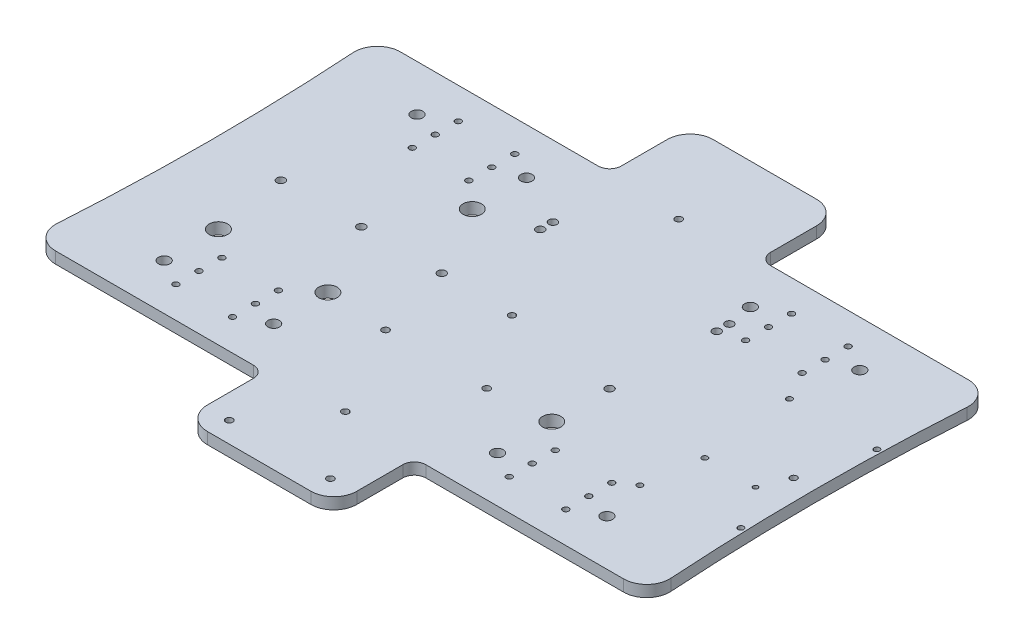
SolidWorks part; units mm, degrees
material "Acrylic (Medium-high impact)"
ref_plane "Front Plane" through (0, 0, 0) normal (0, 0, 1) x (1, 0, 0)
ref_plane "Top Plane" through (0, 0, 0) normal (0, 1, 0) x (1, 0, 0)
ref_plane "Right Plane" through (0, 0, 0) normal (1, 0, 0) x (0, 0, -1)
sketch "Sketch1" plane through (0, 0, 0) normal (0, 1, 0) x (1, 0, 0)
  line L0 (-142.875, -95.25) -> (-41.275, -95.25) construction
  line L2 (-174.625, -152.4) -> (-174.625, -139.7) construction
  line L3 (-174.625, 152.4) -> (-161.925, 152.4) construction
  line L4 (174.625, -152.4) -> (174.625, -139.7) construction
  line L5 (-174.625, -152.4) -> (174.625, 152.4) construction
  line L6 (-174.625, 152.4) -> (174.625, -152.4) construction
  line L7 (-92.075, -92.075) -> (92.075, -92.075) construction
  line L8 (-92.075, -92.075) -> (-92.075, 92.075) construction
  line L9 (-92.075, 92.075) -> (92.075, 92.075) construction
  line L10 (92.075, -92.075) -> (92.075, 92.075) construction
  line L11 (-92.075, -92.075) -> (92.075, 92.075) construction
  line L12 (-92.075, 92.075) -> (92.075, -92.075) construction
  line L13 (41.275, -95.25) -> (142.875, -95.25) construction
  line L14 (-92.075, -95.25) -> (-92.075, 0) construction
  line L15 (92.075, -95.25) -> (92.075, -93.4918) construction
  line L16 (-166.9949, 0) -> (166.9949, 0) construction
  line L17 (41.275, 95.25) -> (142.875, 95.25) construction
  line L18 (92.075, 95.25) -> (92.075, 93.4918) construction
  line L19 (-92.075, 95.25) -> (-92.075, 0) construction
  line L20 (-142.875, 95.25) -> (-41.275, 95.25) construction
  line L21 (-174.625, -152.4) -> (-161.925, -152.4) construction
  line L22 (-142.875, 95.25) -> (-41.275, 95.25)
  line L23 (-142.875, 95.25) -> (-142.875, 139.7) construction
  line L24 (-142.875, 139.7) -> (-41.275, 139.7) construction
  line L25 (-41.275, 95.25) -> (-41.275, 139.7)
  line L26 (41.275, 95.25) -> (142.875, 95.25)
  line L27 (41.275, 95.25) -> (41.275, 139.7)
  line L28 (41.275, 139.7) -> (142.875, 139.7) construction
  line L29 (142.875, 95.25) -> (142.875, 139.7) construction
  line L30 (-107.696, 84.201) -> (-107.696, 34.925) construction
  line L31 (-142.875, -95.25) -> (-41.275, -95.25)
  line L33 (-142.875, -139.7) -> (-41.275, -139.7) construction
  line L34 (-41.275, -95.25) -> (-41.275, -139.7)
  line L35 (41.275, -95.25) -> (142.875, -95.25)
  line L36 (41.275, -95.25) -> (41.275, -139.7)
  line L37 (41.275, -139.7) -> (142.875, -139.7) construction
  line L39 (-110.871, 84.201) -> (-73.279, 84.201) construction
  line L40 (-110.871, 84.201) -> (-110.871, 34.925) construction
  line L41 (-110.871, 34.925) -> (-73.279, 34.925) construction
  line L42 (-73.279, 84.201) -> (-73.279, 34.925) construction
  line L43 (-76.454, 34.925) -> (-76.454, 84.201) construction
  line L44 (0, 148.8387) -> (0, -148.6976) construction
  line L45 (-174.625, 139.7) -> (-174.625, 152.4) construction
  line L46 (174.625, 139.7) -> (174.625, 152.4) construction
  line L49 (161.925, -152.4) -> (174.625, -152.4) construction
  line L50 (161.925, 152.4) -> (174.625, 152.4) construction
  line L51 (142.875, -95.25) -> (170.5718, -95.25)
  line L52 (41.275, -26.67) -> (142.875, -26.67) construction
  line L53 (41.275, -26.67) -> (41.275, 26.67) construction
  line L54 (41.275, 26.67) -> (142.875, 26.67) construction
  line L55 (142.875, -26.67) -> (142.875, 26.67) construction
  line L56 (41.275, -26.67) -> (142.875, 26.67) construction
  line L57 (41.275, 26.67) -> (142.875, -26.67) construction
  line L58 (-31.75, -142.24) -> (31.75, -142.24) construction
  line L62 (-31.75, -85.09) -> (31.75, -85.09) construction
  line L64 (41.275, -139.7) -> (-41.275, -139.7)
  line L65 (-142.875, -95.25) -> (-170.5718, -95.25)
  line L66 (-142.875, 95.25) -> (-170.5718, 95.25)
  line L67 (142.875, 95.25) -> (170.5718, 95.25)
  line L68 (-41.275, 139.7) -> (41.275, 139.7)
  line L69 (-31.75, -132.08) -> (31.75, -132.08) construction
  line L70 (-31.75, -132.08) -> (-31.75, -38.1) construction
  line L71 (-31.75, -38.1) -> (31.75, -38.1) construction
  line L72 (31.75, -132.08) -> (31.75, -38.1) construction
  circle A0 centre (-107.696, 77.978) radius 1.651
  circle A1 centre (-107.696, 71.628) radius 1.651 construction
  circle A2 centre (-107.696, 65.278) radius 1.651
  circle A3 centre (-107.696, 58.928) radius 1.651 construction
  circle A4 centre (-107.696, 52.578) radius 1.651
  circle A5 centre (-107.696, 46.228) radius 1.651 construction
  circle A6 centre (-107.696, 39.878) radius 1.651 construction
  circle A7 centre (-76.454, 77.978) radius 1.651
  circle A8 centre (-76.454, 71.628) radius 1.651 construction
  circle A9 centre (-76.454, 65.278) radius 1.651
  circle A10 centre (-76.454, 58.928) radius 1.651 construction
  circle A11 centre (-76.454, 52.578) radius 1.651
  circle A12 centre (-76.454, 39.878) radius 1.651 construction
  circle A13 centre (-76.454, 46.228) radius 1.651 construction
  circle A14 centre (76.454, 39.878) radius 1.651 construction
  circle A15 centre (107.696, 39.878) radius 1.651 construction
  circle A16 centre (107.696, 46.228) radius 1.651 construction
  circle A17 centre (76.454, 46.228) radius 1.651 construction
  circle A18 centre (76.454, 52.578) radius 1.651
  circle A19 centre (107.696, 52.578) radius 1.651
  circle A20 centre (107.696, 58.928) radius 1.651 construction
  circle A21 centre (76.454, 58.928) radius 1.651 construction
  circle A22 centre (76.454, 65.278) radius 1.651
  circle A23 centre (107.696, 65.278) radius 1.651
  circle A24 centre (107.696, 71.628) radius 1.651 construction
  circle A25 centre (76.454, 71.628) radius 1.651 construction
  circle A26 centre (76.454, 77.978) radius 1.651
  circle A27 centre (107.696, 77.978) radius 1.651
  circle A28 centre (76.454, -39.878) radius 1.651 construction
  circle A29 centre (107.696, -39.878) radius 1.651 construction
  circle A30 centre (107.696, -46.228) radius 1.651 construction
  circle A31 centre (76.454, -46.228) radius 1.651 construction
  circle A32 centre (76.454, -52.578) radius 1.651
  circle A33 centre (107.696, -52.578) radius 1.651
  circle A34 centre (107.696, -58.928) radius 1.651 construction
  circle A35 centre (76.454, -58.928) radius 1.651 construction
  circle A36 centre (107.696, -65.278) radius 1.651
  circle A37 centre (76.454, -65.278) radius 1.651
  circle A38 centre (76.454, -71.628) radius 1.651 construction
  circle A39 centre (107.696, -71.628) radius 1.651 construction
  circle A40 centre (107.696, -77.978) radius 1.651
  circle A41 centre (76.454, -77.978) radius 1.651
  circle A42 centre (-76.454, -39.878) radius 1.651 construction
  circle A43 centre (-107.696, -39.878) radius 1.651 construction
  circle A44 centre (-107.696, -46.228) radius 1.651 construction
  circle A45 centre (-76.454, -46.228) radius 1.651 construction
  circle A46 centre (-76.454, -52.578) radius 1.651
  circle A47 centre (-107.696, -52.578) radius 1.651
  circle A48 centre (-107.696, -58.928) radius 1.651 construction
  circle A49 centre (-76.454, -58.928) radius 1.651 construction
  circle A50 centre (-76.454, -65.278) radius 1.651
  circle A51 centre (-107.696, -65.278) radius 1.651
  circle A52 centre (-107.696, -71.628) radius 1.651 construction
  circle A53 centre (-76.454, -71.628) radius 1.651 construction
  circle A54 centre (-76.454, -77.978) radius 1.651
  circle A55 centre (-107.696, -77.978) radius 1.651
  arc A56 (-160.8132, 152.3512) -> (-174.5495, 138.3168) centre (-161.925, 139.7) ccw construction
  arc A57 (-160.7914, -152.3493) -> (-174.5495, -138.3168) centre (-161.925, -139.7) cw construction
  arc A58 (-174.5495, 138.3168) -> (-174.5495, -138.3168) centre (-1436.9949, 0) cw construction
  arc A59 (160.7914, -152.3493) -> (174.5495, -138.3168) centre (161.925, -139.7) ccw construction
  arc A60 (174.5495, 138.3168) -> (174.5495, -138.3168) centre (1436.9949, 0) ccw construction
  arc A61 (160.8132, 152.3512) -> (174.5495, 138.3168) centre (161.925, 139.7) cw construction
  arc A62 (-161.925, 152.4) -> (161.925, 152.4) centre (0, 3831.8387) ccw construction
  circle A64 centre (-161.925, 139.7) radius 1.8415 construction
  circle A65 centre (-161.925, -139.7) radius 1.8415 construction
  circle A66 centre (161.925, -139.7) radius 1.8415 construction
  circle A67 centre (161.925, 139.7) radius 1.8415 construction
  circle A68 centre (56.515, 24.13) radius 1.5875 construction
  circle A69 centre (55.245, -24.13) radius 1.5875 construction
  circle A70 centre (138.2395, -24.13) radius 1.5875 construction
  circle A71 centre (131.445, 24.13) radius 1.5875 construction
  circle A72 centre (107.315, 8.89) radius 1.5875 construction
  circle A73 centre (107.315, -19.05) radius 1.5875 construction
  circle A82 centre (161.925, 93.98) radius 1.8415 construction
  circle A84 centre (161.925, -93.98) radius 1.8415 construction
  circle A86 centre (155.575, 0) radius 1.8415
  arc A88 (-170.5718, -95.25) -> (-170.5718, 95.25) centre (-1436.9949, 0) ccw
  arc A89 (170.5718, 95.25) -> (170.5718, -95.25) centre (1436.9949, 0) ccw
  circle A90 centre (-27.94, -128.27) radius 1.905
  circle A91 centre (27.94, -128.27) radius 1.905
  circle A92 centre (-27.94, -41.91) radius 1.905
  circle A93 centre (27.94, -41.91) radius 1.905
  circle A94 centre (27.94, 41.91) radius 1.905 construction
  circle A95 centre (-27.94, 41.91) radius 1.905 construction
  circle A96 centre (-27.94, 128.27) radius 1.905 construction
  circle A97 centre (27.94, 128.27) radius 1.905 construction
  circle A98 centre (0, 0) radius 1.8415
  circle A99 centre (-157.8718, 82.55) radius 1.8415 construction
  circle A100 centre (-157.8718, -82.55) radius 1.8415 construction
  circle A101 centre (157.8718, -82.55) radius 1.8415 construction
  circle A102 centre (157.8718, 82.55) radius 1.8415 construction
  circle A103 centre (-122.3118, 69.85) radius 3.175
  circle A108 centre (-61.8382, 69.85) radius 3.175
  circle A113 centre (-61.8382, -69.85) radius 3.175
  circle A114 centre (-122.3118, -69.85) radius 3.175
  circle A115 centre (61.8382, -69.85) radius 3.175
  circle A116 centre (122.3118, -69.85) radius 3.175
  circle A117 centre (61.8382, 69.85) radius 3.175
  circle A118 centre (122.3118, 69.85) radius 3.175
  circle A125 centre (149.4807, -14.9479) radius 1.3153
  circle A126 centre (121.4645, -14.9479) radius 1.5621
  circle A127 centre (116.586, -45.9486) radius 1.5621
  circle A128 centre (164.9222, -38.4556) radius 1.5621
  circle A129 centre (164.9222, 36.6776) radius 1.5621
  circle A130 centre (116.586, 36.6776) radius 1.5621
  circle A131 centre (0, -92.075) radius 1.905
  circle A132 centre (0, 92.075) radius 1.905
  circle A133 centre (-61.8382, -39.878) radius 5.08
  circle A134 centre (-122.3118, -39.878) radius 5.08
  circle A135 centre (122.3118, -39.878) radius 5.08 construction
  circle A136 centre (61.8382, -39.878) radius 5.08
  circle A140 centre (62.0269, -8.1282) radius 2.2479
  circle A141 centre (64.1769, 48.9244) radius 2.2479
  circle A142 centre (64.1769, 55.9244) radius 2.2479
  circle A143 centre (-33.3231, 55.9244) radius 2.2479
  circle A144 centre (-33.3231, 48.9244) radius 2.2479
  circle A145 centre (-44.3356, 36.3244) radius 2.2479 construction
  circle A146 centre (-39.5731, 0.7618) radius 2.2479
  circle A147 centre (-84.0231, 0.7618) radius 2.2479
  circle A148 centre (-128.4731, 0.7618) radius 2.2479
  point P0 (0, 0)
  point P6 (0, 0)
  point P37 (-92.075, 84.201)
  point P188 (92.075, 0)
  point P205 (0, -92.075)
  dimension "D17" = 3.302
  dimension "D19" = 4.953
  dimension "D21" = 25.4
  dimension "D22" = 1270
  dimension "D23" = 3683
  dimension "D24" = 3.683
  dimension "D25" = 3.683
  dimension "D26" = 3.683
  dimension "D27" = 3.683
  dimension "D31" = 3.175
  dimension "D42" = 93.98
  dimension "D48" = 3.683
  dimension "D50" = 3.683
  dimension "D51" = 3.81
  dimension "D52" = 3.81
  dimension "D57" = 3.683
  dimension "D60" = 6.35
  dimension "D62" = 10.16
  dimension "D64" = 58.5724
  dimension "D65" = 61.8382
  dimension "D66" = 60.4736
  dimension "D1" = 349.25
  dimension "D2" = 304.8
  dimension "D3" = 101.6
  dimension "D4" = 101.6
  dimension "D5" = 184.15
  dimension "D6" = 190.5
  dimension "D7" = 190.5
  dimension "D8" = 44.45
  dimension "D9" = 44.45
  dimension "D10" = 44.45
  dimension "D11" = 44.45
  dimension "D12" = 7.874
  dimension "D13" = 49.276
  dimension "D14" = 37.592
  dimension "D15" = 31.242
  dimension "D16" = 15.621
  dimension "D20" = 6.35
  dimension "D28" = 101.6
  dimension "D29" = 53.34
  dimension "D30" = 15.24
  dimension "D32" = 13.97
  dimension "D33" = 2.54
  dimension "D34" = 5.08
  dimension "D35" = 27.94
  dimension "D36" = 50.8
  dimension "D37" = 15.24
  dimension "D38" = 24.13
  dimension "D39" = 4.6355
  dimension "D40" = 63.5
  dimension "D41" = 31.75
  dimension "D43" = 7.62
  dimension "D44" = 44.45
  dimension "D45" = 19.05
  dimension "D46" = 45.72
  dimension "D47" = 19.05
  dimension "D49" = 12.7
  dimension "D53" = 3.81
  dimension "D54" = 3.81
  dimension "D55" = 3.81
  dimension "D56" = 3.81
  dimension "D58" = 12.7
  dimension "D59" = 12.7
  dimension "D61" = 35.56
  dimension "D63" = 25.4
  dimension "D18" = 7
extrude "Boss-Extrude1" add sketch "Sketch1" along normal blind 6.35
fillet "Fillet_Outer_Corners" radius 12.7 8 edges at (-170.5718, 3.175, -95.25) (-41.275, 3.175, -139.7) (41.275, 3.175, -139.7) (170.5718, 3.175, -95.25) (170.5718, 3.175, 95.25) (41.275, 3.175, 139.7) (-41.275, 3.175, 139.7) (-170.5718, 3.175, 95.25)
fillet "Fillet_Inner_Corners" radius 6.35 4 edges at (41.275, 3.175, -95.25) (-41.275, 3.175, -95.25) (41.275, 3.175, 95.25) (-41.275, 3.175, 95.25)
ref_plane "Mirror Plane1" through (0, 0, 0) normal (-1, 0, 0) x (0, 0, 1)
sketch "Sketch2" plane through (0, 6.35, 0) normal (0, 1, 0) x (1, 0, 0)
  line L0 (0, 0) -> (-98.3387, 0) construction
  circle A0 centre (-61.8382, -39.878) radius 5.08 construction
  circle A1 centre (-61.8382, -39.878) radius 5.08 construction
  circle A2 centre (-61.8382, 39.878) radius 5.08
extrude "Cut-Extrude1" cut sketch "Sketch2" against normal through all
